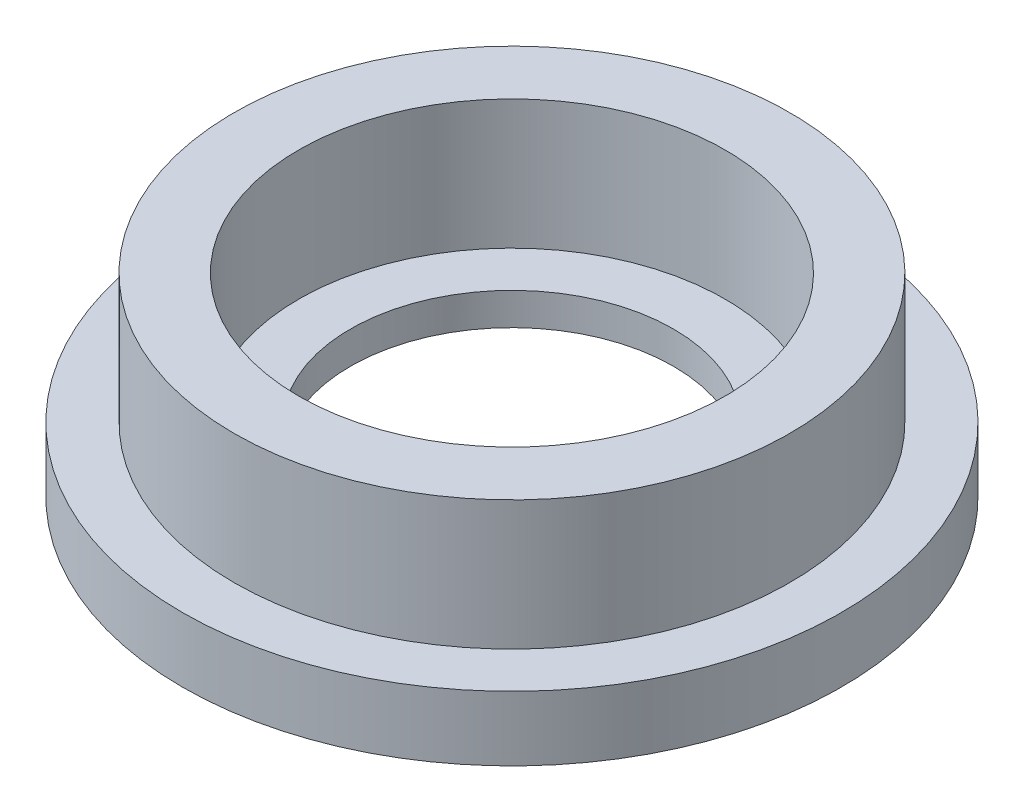
SolidWorks part; units mm, degrees
ref_plane "Front Plane" through (0, 0, 0) normal (0, 0, 1) x (1, 0, 0)
ref_plane "Top Plane" through (0, 0, 0) normal (0, 1, 0) x (1, 0, 0)
ref_plane "Right Plane" through (0, 0, 0) normal (1, 0, 0) x (0, 0, -1)
sketch "Sketch1" plane through (0, 0, 0) normal (0, 1, 0) x (1, 0, 0)
  circle A0 centre (0, 0) radius 5.1
  dimension "D1" = 10.2
extrude "Boss-Extrude1" add sketch "Sketch1" along normal blind 1 contours A0
sketch "Sketch2" plane through (0, 1, 0) normal (0, 1, 0) x (1, 0, 0)
  circle A0 centre (0, 0) radius 4.3
  circle A1 centre (0, 0) radius 3.3
  dimension "D1" = 8.6
  dimension "D2" = 6.6
extrude "Boss-Extrude2" add sketch "Sketch2" along normal blind 2
sketch "Sketch3" plane through (0, 0, 0) normal (0, -1, 0) x (1, 0, 0)
  circle A0 centre (0, 0) radius 2.5
  dimension "D1" = 5
extrude "Cut-Extrude1" cut sketch "Sketch3" against normal blind 2
sketch "Sketch4" plane through (0, 0, 0) normal (0, -1, 0) x (1, 0, 0)
  circle A0 centre (0, 0) radius 4.5
  dimension "D1" = 9
extrude "Cut-Extrude2" cut sketch "Sketch4" against normal blind 0.5
